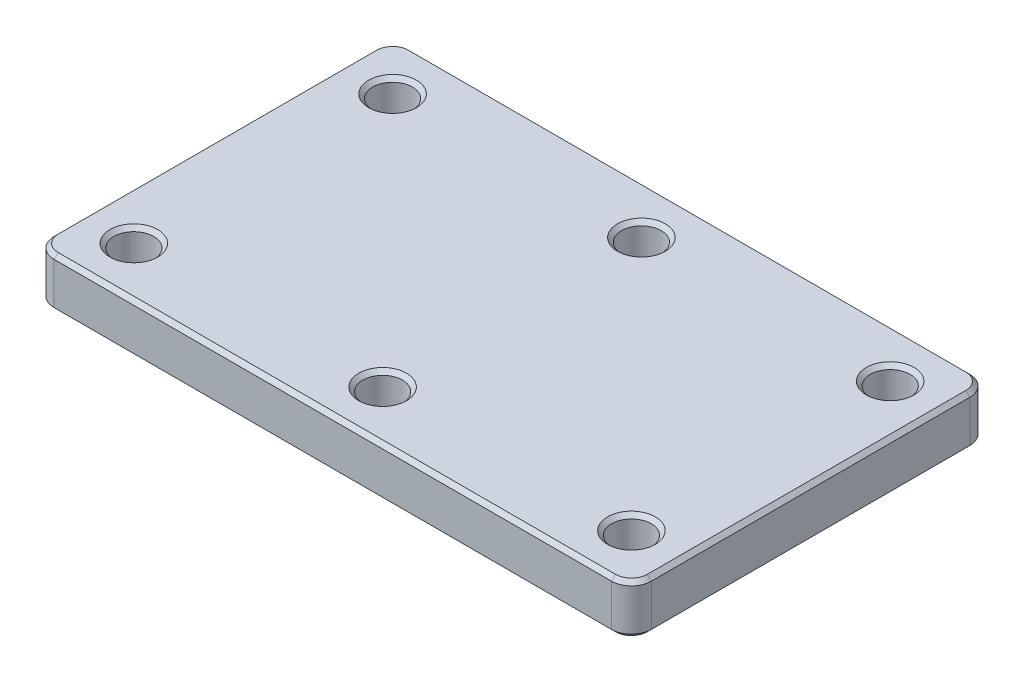
SolidWorks part; units mm, degrees
ref_plane "Front Plane" through (0, 0, 0) normal (0, 0, 1) x (1, 0, 0)
ref_plane "Top Plane" through (0, 0, 0) normal (0, 1, 0) x (1, 0, 0)
ref_plane "Right Plane" through (0, 0, 0) normal (1, 0, 0) x (0, 0, -1)
sketch "Sketch1" plane through (0, 0, 0) normal (0, 1, 0) x (1, 0, 0)
  line L1 (10, 0) -> (290, 0)
  line L2 (0, 10) -> (0, 170)
  line L3 (10, 180) -> (290, 180)
  line L4 (300, 10) -> (300, 170)
  arc A0 (290, 180) -> (300, 170) centre (290, 170) cw
  arc A1 (290, 0) -> (300, 10) centre (290, 10) ccw
  arc A2 (10, 0) -> (0, 10) centre (10, 10) cw
  arc A3 (0, 170) -> (10, 180) centre (10, 170) cw
  circle A4 centre (25, 155) radius 10
  circle A5 centre (150, 155) radius 10
  circle A6 centre (275, 155) radius 10
  circle A7 centre (150, 25) radius 10
  circle A8 centre (275, 25) radius 10
  circle A9 centre (25, 25) radius 10
  point P11 (0, 0)
  point P16 (0, 0)
  point P17 (150, 180)
  point P18 (0, 0)
  point P29 (0, 90)
  point P30 (0, 0)
  point P31 (150, 0)
  dimension "D3" = 10
  dimension "D4" = 20
  dimension "D1" = 300
  dimension "D2" = 180
  dimension "D7" = 65
  dimension "D8" = 130
  dimension "D9" = 250
  dimension "D5" = 3
  dimension "D6" = 2
extrude "Boss-Extrude1" add sketch "Sketch1" along normal blind 25
chamfer "Chamfer1" distance 2 angle 45 14 edges at (25, 25, -15) (275, 25, -15) (150, 25, -15) (275, 25, -145) (150, 25, -145) (25, 25, -145) (300, 25, -90) (297.0711, 25, -2.9289) (150, 25, 0) (2.9289, 25, -2.9289) (0, 25, -90) (2.9289, 25, -177.0711) (150, 25, -180) (297.0711, 25, -177.0711)
chamfer "Chamfer2" distance 2 angle 45 14 edges at (25, 0, -15) (150, 0, -15) (150, 0, -145) (150, 0, -180) (2.9289, 0, -177.0711) (0, 0, -90) (2.9289, 0, -2.9289) (150, 0, 0) (297.0711, 0, -2.9289) (300, 0, -90) (297.0711, 0, -177.0711) (25, 0, -145) (275, 0, -145) (275, 0, -15)
